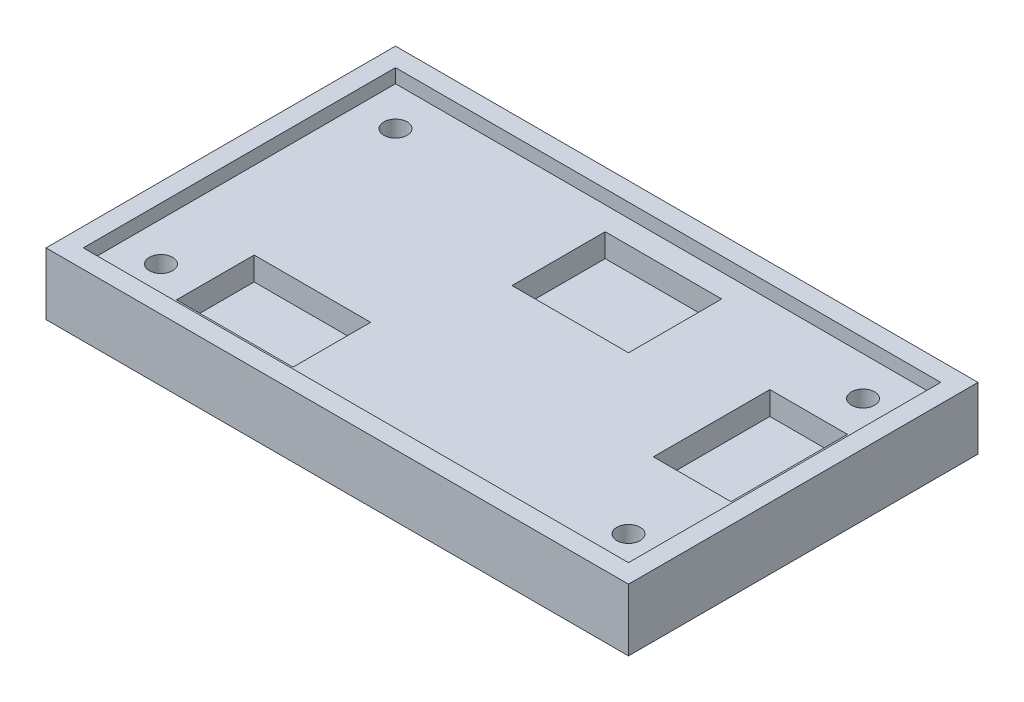
SolidWorks part; units mm, degrees
ref_plane "前视基准面" through (0, 0, 0) normal (0, 0, 1) x (1, 0, 0)
ref_plane "上视基准面" through (0, 0, 0) normal (0, 1, 0) x (1, 0, 0)
ref_plane "右视基准面" through (0, 0, 0) normal (1, 0, 0) x (0, 0, -1)
other "Configuration Table"
sketch "草图2" plane through (0, 0, 0) normal (0, 1, 0) x (1, 0, 0)
  line L1 (0, 0) -> (75, 0)
  line L2 (0, 0) -> (0, 45)
  line L3 (0, 45) -> (75, 45)
  line L4 (75, 0) -> (75, 45)
  dimension "D2" = 45
  dimension "D3" = 75
extrude "凸台-拉伸3" add sketch "草图2" along normal blind 8 contours L2 L1 L4 L3
sketch "草图5" plane through (0, 8, 0) normal (0, 1, 0) x (1, 0, 0)
  line L9 (2.4, 2.4) -> (72.6, 2.4)
  line L10 (72.6, 2.4) -> (72.6, 42.6)
  line L11 (72.6, 42.6) -> (2.4, 42.6)
  line L12 (2.4, 42.6) -> (2.4, 2.4)
  line L13 (2.4, 2.4) -> (72.6, 2.4)
  line L14 (72.6, 2.4) -> (72.6, 42.6)
  line L15 (72.6, 42.6) -> (2.4, 42.6)
  line L16 (2.4, 42.6) -> (2.4, 2.4)
  dimension "D1" = 2.4
extrude "切除-拉伸1" cut sketch "草图5" against normal blind 1.8 contours L13 L14 L15 L16
sketch "草图7" plane through (0, 6.2, 0) normal (0, 1, 0) x (1, 0, 0)
  line L0 (2.4, 42.6) -> (2.4, 2.4) construction
  line L1 (72.6, 42.6) -> (2.4, 42.6) construction
  line L6 (37.5, 42.5) -> (37.5, 50.7498) construction
  line L8 (2.5, 22.5) -> (6.7449, 22.5) construction
  circle A0 centre (7.4, 37.6) radius 1.5
  circle A1 centre (67.6, 37.6) radius 1.5
  circle A2 centre (7.4, 7.4) radius 1.5
  circle A3 centre (67.6, 7.4) radius 1.5
  dimension "D1" = 3
  dimension "D2" = 5
  dimension "D3" = 5
extrude "切除-拉伸4" cut sketch "草图7" against normal blind 2.2
sketch "草图8" plane through (0, 6.2, 0) normal (0, 1, 0) x (1, 0, 0)
  line L0 (2.4, 42.6) -> (2.4, 2.4) construction
  line L1 (12.4, 14.4) -> (27.4, 14.4)
  line L2 (12.4, 14.4) -> (12.4, 4.4)
  line L3 (12.4, 4.4) -> (27.4, 4.4)
  line L4 (27.4, 14.4) -> (27.4, 4.4)
  line L5 (2.4, 2.4) -> (72.6, 2.4) construction
  line L6 (2.4, 2.4) -> (72.6, 2.4) construction
  line L7 (72.6, 42.6) -> (2.4, 42.6) construction
  line L8 (60.6, 32.6) -> (70.6, 32.6)
  line L9 (60.6, 32.6) -> (60.6, 17.6)
  line L10 (60.6, 17.6) -> (70.6, 17.6)
  line L11 (70.6, 32.6) -> (70.6, 17.6)
  line L12 (72.6, 2.4) -> (72.6, 42.6) construction
  line L13 (72.6, 2.4) -> (72.6, 42.6) construction
  line L14 (72.6, 42.6) -> (2.4, 42.6) construction
  line L15 (32.4, 39.6) -> (47.4, 39.6)
  line L16 (32.4, 39.6) -> (32.4, 27.6)
  line L17 (32.4, 27.6) -> (47.4, 27.6)
  line L18 (47.4, 39.6) -> (47.4, 27.6)
  line L19 (2.4, 42.6) -> (2.4, 2.4) construction
  dimension "D1" = 10
  dimension "D2" = 15
  dimension "D3" = 2
  dimension "D4" = 12
  dimension "D5" = 25
  dimension "D6" = 12
  dimension "D7" = 2
  dimension "D8" = 10
  dimension "D9" = 30
  dimension "D10" = 15
  dimension "D11" = 3
  dimension "D12" = 45
extrude "切除-拉伸6" cut sketch "草图8" against normal blind 3
